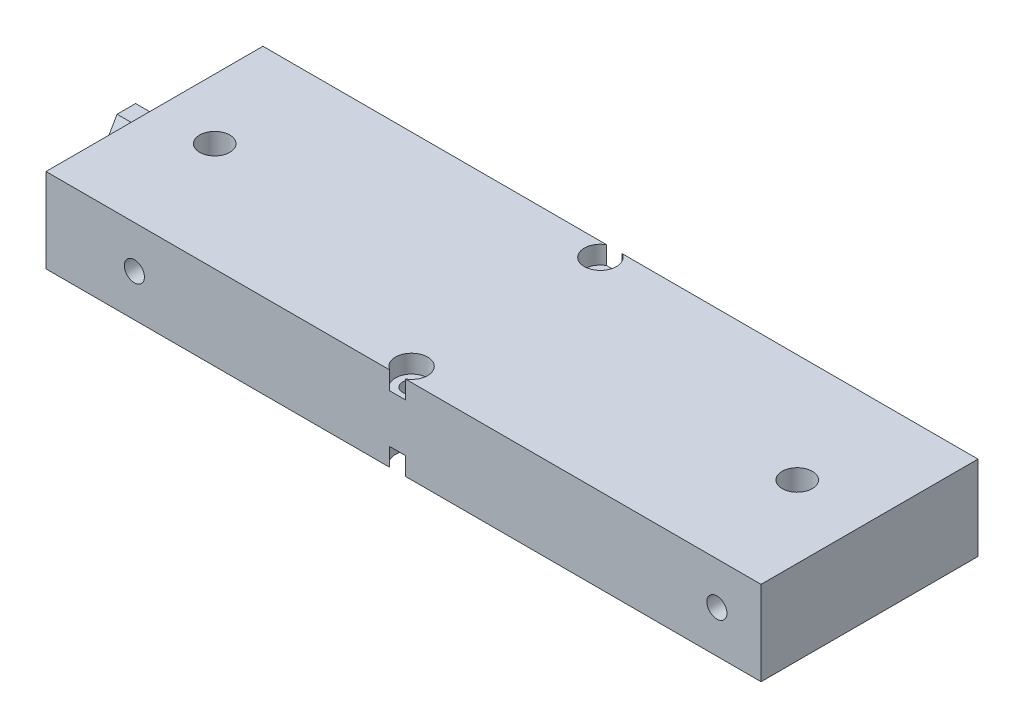
SolidWorks part; units mm, degrees
ref_plane "前视基准面" through (0, 0, 0) normal (0, 0, 1) x (1, 0, 0)
ref_plane "上视基准面" through (0, 0, 0) normal (0, 1, 0) x (1, 0, 0)
ref_plane "右视基准面" through (0, 0, 0) normal (1, 0, 0) x (0, 0, -1)
sketch "草图1" plane through (0, 0, 0) normal (0, 1, 0) x (1, 0, 0)
  line L1 (0, 0) -> (178, 0)
  line L2 (0, 0) -> (0, 54)
  line L3 (0, 54) -> (178, 54)
  line L4 (178, 0) -> (178, 54)
  dimension "D1" = 178
  dimension "D2" = 54
extrude "凸台-拉伸1" add sketch "草图1" along normal blind 21
sketch "草图2" plane through (0, 0, 0) normal (-1, 0, 0) x (0, 0, 1)
  line L0 (-27, 21) -> (-27, 0) construction
  line L1 (-54, 21) -> (0, 21) construction
  line L2 (-54, 0) -> (0, 0) construction
  circle A0 centre (-15, 10.5) radius 4
  circle A1 centre (-39, 10.5) radius 4
  point P6 (-27, 10.5)
  dimension "D1" = 8
  dimension "D2" = 24
extrude "切除-拉伸1" cut sketch "草图2" against normal blind 125
sketch "草图3" plane through (0, 21, 0) normal (0, 1, 0) x (1, 0, 0)
  line L0 (0, 27) -> (178, 27) construction
  line L1 (0, 54) -> (0, 0) construction
  line L2 (178, 0) -> (178, 54) construction
  circle A0 centre (87.5, 3.5) radius 2.25
  circle A1 centre (87.5, 50.5) radius 2.25
  circle A2 centre (15, 27) radius 2.25
  circle A3 centre (160, 27) radius 2.25
  dimension "D1" = 47
  dimension "D2" = 4.5
  dimension "D3" = 87.5
  dimension "D4" = 4.5
  dimension "D5" = 4.5
  dimension "D7" = 145
  dimension "D6" = 15
extrude "切除-拉伸2" cut sketch "草图3" against normal through all
sketch "草图4" plane through (0, 21, 0) normal (0, 1, 0) x (1, 0, 0)
  circle A1 centre (87.5, 50.5) radius 4
  circle A2 centre (87.5, 3.5) radius 4
  circle A4 centre (87.5, 50.5) radius 2.25 construction
  dimension "D3" = 8
  dimension "D4" = 8
extrude "切除-拉伸3" cut sketch "草图4" against normal blind 4.5
sketch "草图5" plane through (0, 21, 0) normal (0, 1, 0) x (1, 0, 0)
  circle A0 centre (160, 27) radius 3.75
  circle A1 centre (15, 27) radius 3.75
  dimension "D1" = 7.5
  dimension "D2" = 7.5
extrude "切除-拉伸4" cut sketch "草图5" against normal blind 7.2
ref_plane "基准面1" through (0, 10.5, 0) normal (0, -1, 0) x (-1, 0, 0)
mirror "镜向1" about plane through (0, 10.5, 0) normal (0, -1, 0) of "切除-拉伸3", "切除-拉伸4"
sketch "草图6" plane through (0, 0, 0) normal (0, 0, 1) x (1, 0, 0)
  line L0 (0, 10.5) -> (178, 10.5) construction
  line L1 (0, 21) -> (0, 0) construction
  line L2 (178, 21) -> (178, 0) construction
  circle A0 centre (22, 10.5) radius 2.5
  circle A1 centre (167, 10.5) radius 2.5
  dimension "D1" = 5
  dimension "D2" = 5
  dimension "D3" = 22
  dimension "D4" = 11
extrude "切除-拉伸5" cut sketch "草图6" against normal blind 5
cosmetic thread "装饰螺纹线1" parameters "D2"=6
cosmetic thread "装饰螺纹线2" parameters "D2"=6
sketch "草图7" plane through (0, 0, 0) normal (-1, 0, 0) x (0, 0, 1)
  line L0 (0, 10.5) -> (-54, 10.5) construction
  line L1 (0, 21) -> (0, 0) construction
  line L2 (-54, 21) -> (-54, 0) construction
  line L3 (-27, 10.5) -> (-27, 13.5) construction
  line L5 (-24.6906, 17.5) -> (-29.3094, 17.5)
  line L6 (-29.3094, 17.5) -> (-31.6188, 13.5)
  line L7 (-31.6188, 13.5) -> (-29.3094, 9.5)
  line L8 (-29.3094, 9.5) -> (-24.6906, 9.5)
  line L9 (-24.6906, 9.5) -> (-22.3812, 13.5)
  line L10 (-22.3812, 13.5) -> (-24.6906, 17.5)
  circle A0 centre (-27, 13.5) radius 4 construction
  circle A1 centre (-27, 13.5) radius 4.6188 construction
  point P9 (-27, 17.5)
  point P17 (-27, 17.5)
  dimension "D2" = 8
  dimension "D1" = 3
extrude "凸台-拉伸2" add sketch "草图7" along normal blind 7
